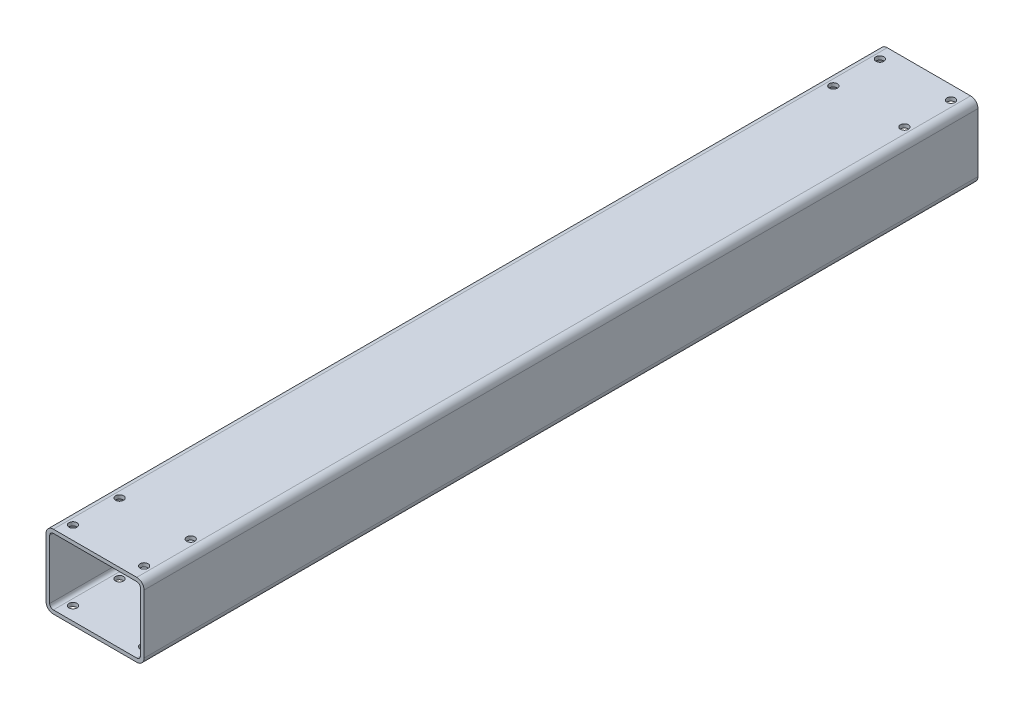
SolidWorks part; units mm, degrees
ref_plane "Front Plane" through (0, 0, 0) normal (0, 0, 1) x (1, 0, 0)
ref_plane "Top Plane" through (0, 0, 0) normal (0, 1, 0) x (1, 0, 0)
ref_plane "Right Plane" through (0, 0, 0) normal (1, 0, 0) x (0, 0, -1)
sketch "Sketch1" plane through (0, 0, 0) normal (0, 0, 1) x (1, 0, 0)
  line L0 (-40, -24) -> (-40, 24)
  line L1 (-34, -30) -> (34, -30)
  line L2 (-34, 30) -> (34, 30)
  line L3 (40, -24) -> (40, 24)
  line L4 (-40, -30) -> (40, 30) construction
  line L5 (-40, 30) -> (40, -30) construction
  line L6 (-34, 27) -> (34, 27)
  line L7 (37, -24) -> (37, 24)
  line L8 (-34, -27) -> (34, -27)
  line L9 (-37, -24) -> (-37, 24)
  arc A0 (-34, -30) -> (-40, -24) centre (-34, -24) cw
  arc A1 (40, -24) -> (34, -30) centre (34, -24) cw
  arc A2 (40, 24) -> (34, 30) centre (34, 24) ccw
  arc A3 (-40, 24) -> (-34, 30) centre (-34, 24) cw
  arc A4 (37, 24) -> (34, 27) centre (34, 24) ccw
  arc A5 (37, -24) -> (34, -27) centre (34, -24) cw
  arc A6 (-34, -27) -> (-37, -24) centre (-34, -24) cw
  arc A7 (-37, 24) -> (-34, 27) centre (-34, 24) cw
  point P1 (0, 0)
  dimension "D3" = 6
  dimension "D1" = 80
  dimension "D2" = 60
  dimension "D4" = 3
extrude "Boss-Extrude1" add sketch "Sketch1" along normal blind 680
sketch "Sketch2" plane through (0, 30, 0) normal (0, 1, 0) x (1, 0, 0)
  line L0 (-34, -340) -> (34, -340) construction
  line L1 (-34, -680) -> (-34, 0) construction
  line L2 (34, -680) -> (34, 0) construction
  line L3 (34, 0) -> (-34, 0) construction
  line L4 (-29, -11) -> (29, -11) construction
  line L5 (-29, -11) -> (-29, -49) construction
  line L6 (-29, -49) -> (29, -49) construction
  line L7 (29, -11) -> (29, -49) construction
  line L8 (29, -669) -> (29, -631) construction
  line L9 (-29, -631) -> (29, -631) construction
  line L10 (-29, -669) -> (-29, -631) construction
  line L11 (-29, -669) -> (29, -669) construction
  point P12 (0, -11)
  dimension "D1" = 58
  dimension "D2" = 38
  dimension "D3" = 11
hole_wizard "Hole1" positions "3DSketch1" profile "Sketch3" legacy end condition through all
sketch3d "3DSketch1"
  point P0 (-29, 30, 669)
  point P3 (-29, 30, 631)
  point P6 (29, 30, 631)
  point P9 (29, 30, 669)
  point P12 (-29, 30, 11)
  point P15 (-29, 30, 49)
  point P18 (29, 30, 11)
  point P21 (29, 30, 49)
sketch "Sketch3" plane through (-29, 30, 669) normal (1, 0, 0) x (0, 0, 1)
  line L0 (0, 0) -> (0, 60)
  line L1 (0, 60) -> (3.25, 60)
  line L2 (3.25, 60) -> (3.25, 0)
  line L3 (3.25, 0) -> (0, 0)
  line L4 (0, 110) -> (0, -10) construction
  dimension "Diameter" = 6.5
  dimension "Depth" = 60
